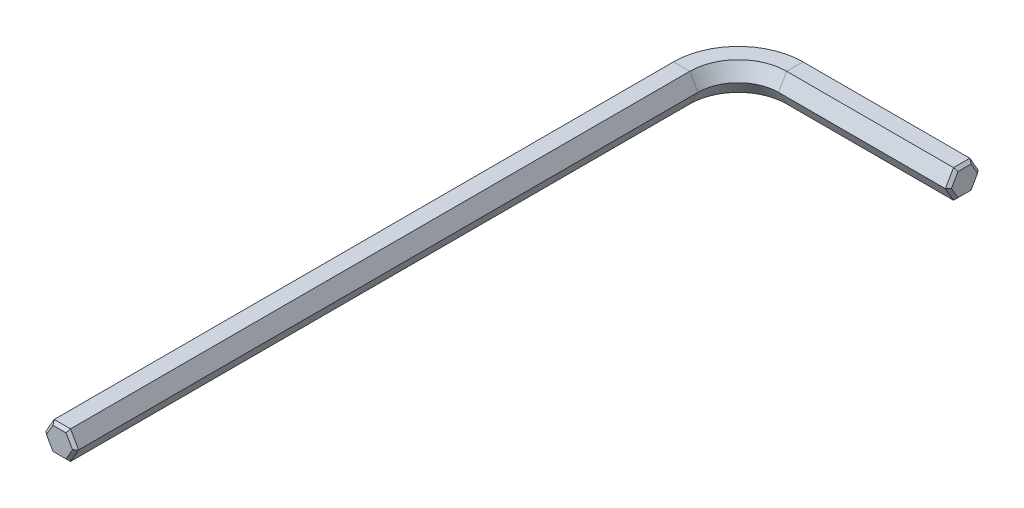
SolidWorks part; units mm, degrees
ref_plane "Front Plane" through (0, 0, 0) normal (0, 0, 1) x (1, 0, 0)
ref_plane "Top Plane" through (0, 0, 0) normal (0, 1, 0) x (1, 0, 0)
ref_plane "Right Plane" through (0, 0, 0) normal (1, 0, 0) x (0, 0, -1)
sketch "Sketch1" plane through (0, 0, 0) normal (0, 0, 1) x (1, 0, 0)
  line L1 (0.7217, 1.25) -> (-0.7217, 1.25)
  line L2 (-0.7217, 1.25) -> (-1.4434, 0)
  line L3 (-1.4434, 0) -> (-0.7217, -1.25)
  line L4 (-0.7217, -1.25) -> (0.7217, -1.25)
  line L5 (0.7217, -1.25) -> (1.4434, 0)
  line L6 (1.4434, 0) -> (0.7217, 1.25)
  circle A0 centre (0, 0) radius 1.25 construction
  dimension "D1" = 2.5
sketch "Sketch2" plane through (0, 0, 0) normal (0, 1, 0) x (1, 0, 0)
  line L0 (0, 0) -> (0, 55)
  line L1 (5, 60) -> (20, 60)
  arc A0 (0, 55) -> (5, 60) centre (5, 55) cw
  point P6 (0, 60)
  dimension "D3" = 5
  dimension "D1" = 60
  dimension "D2" = 20
sweep "Sweep1" add profiles "Sketch1" path "Sketch2"
chamfer "Chamfer1" distance 0.25 6 edges at (20, 0.625, -58.9175) (20, -0.625, -58.9175) (20, -1.25, -60) (20, -0.625, -61.0825) (20, 0.625, -61.0825) (20, 1.25, -60)
chamfer "Chamfer2" distance 0.25 6 edges at (1.0825, -0.625, 0) (0, -1.25, 0) (-1.0825, -0.625, 0) (-1.0825, 0.625, 0) (0, 1.25, 0) (1.0825, 0.625, 0)
